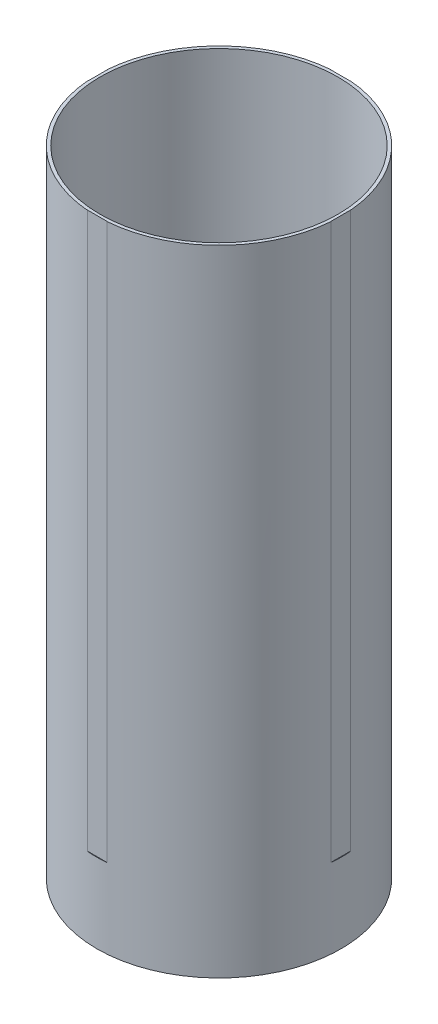
SolidWorks part; units mm, degrees
material "Dragonplate CF"
ref_plane "Front Plane" through (0, 0, 0) normal (0, 0, 1) x (1, 0, 0)
ref_plane "Top Plane" through (0, 0, 0) normal (0, 1, 0) x (1, 0, 0)
ref_plane "Right Plane" through (0, 0, 0) normal (1, 0, 0) x (0, 0, -1)
sketch "Sketch1" plane through (0, 0, 0) normal (0, 1, 0) x (1, 0, 0)
  circle A0 centre (0, 0) radius 76.2
  circle A1 centre (0, 0) radius 78.232
extrude "Boss-Extrude1" add sketch "Sketch1" along normal blind 406.4
ref_plane "Plane1" through (78.232, 0, 0) normal (1, 0, 0) x (0, 0, -1)
sketch "Sketch2" plane through (78.232, 0, 0) normal (1, 0, 0) x (0, 0, -1)
  line L0 (0, 427.2899) -> (0, -2.3142) construction
  line L1 (0, 406.4) -> (6.35, 406.4)
  line L2 (78.232, 406.4) -> (-78.232, 406.4) construction
  line L3 (6.35, 406.4) -> (6.35, 50.8)
  line L4 (6.35, 50.8) -> (-6.35, 50.8)
  line L5 (-6.35, 50.8) -> (-6.35, 406.4)
  line L6 (76.2, 406.4) -> (-76.2, 406.4) construction
  line L7 (-6.35, 406.4) -> (0, 406.4)
extrude "Cut-Extrude1" cut sketch "Sketch2" against normal blind 0.381
pattern_circular "CirPattern1" count 4 over 360 about axis through (0, 0, 0) along (0, 1, 0) of "Cut-Extrude1"
